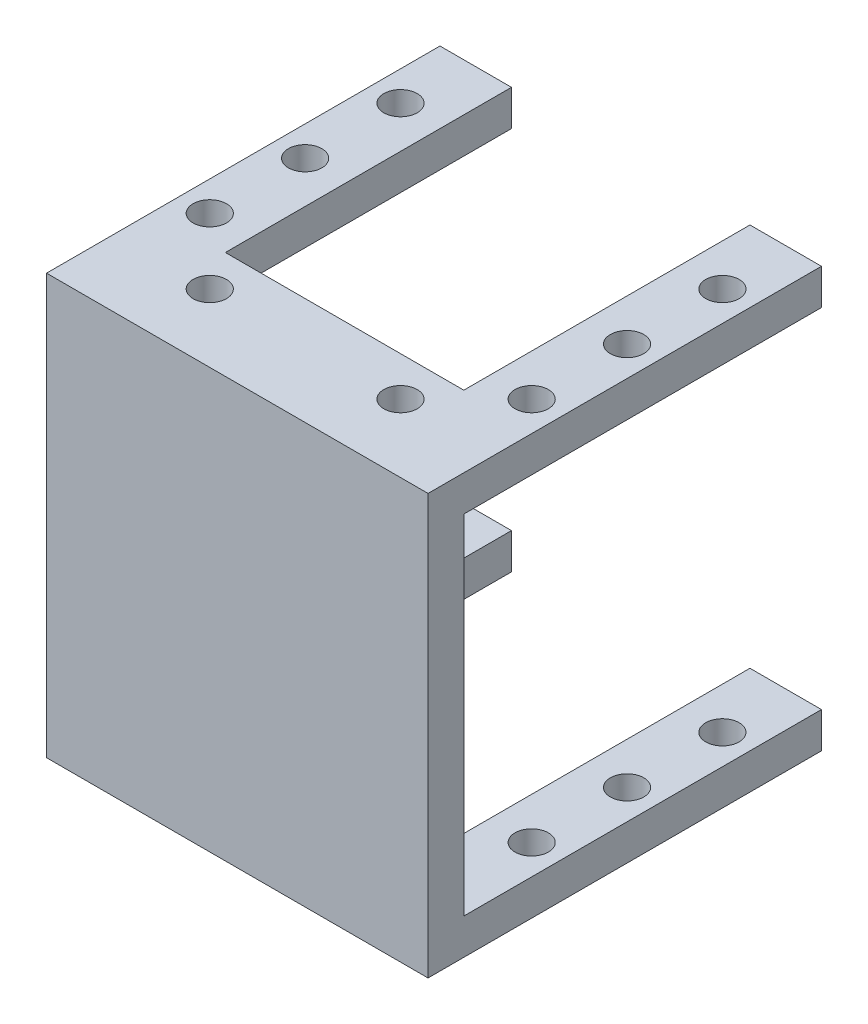
SolidWorks part; units mm, degrees
ref_plane "Front Plane" through (0, 0, 0) normal (0, 0, 1) x (1, 0, 0)
ref_plane "Top Plane" through (0, 0, 0) normal (0, 1, 0) x (1, 0, 0)
ref_plane "Right Plane" through (0, 0, 0) normal (1, 0, 0) x (0, 0, -1)
sketch "Sketch1" plane through (0, 0, 0) normal (0, 1, 0) x (1, 0, 0)
  line L0 (-16, 24) -> (-16, -6)
  line L1 (-16, -6) -> (16, -6)
  line L2 (16, -6) -> (16, 24)
  line L3 (16, 24) -> (10, 24)
  line L4 (10, 24) -> (10, 0)
  line L5 (10, 0) -> (-10, 0)
  line L6 (-10, 0) -> (-10, 24)
  line L7 (-10, 24) -> (-16, 24)
  line L8 (0, 0) -> (0, -6) construction
  circle A0 centre (-0.0169, 32.6923) radius 11 construction
  circle A1 centre (-8, -3.3077) radius 1.4
  circle A2 centre (8, -3.3077) radius 1.4
  circle A3 centre (-13.5, 26.1923) radius 1.4 construction
  circle A4 centre (-13.5, 18.1923) radius 1.4
  circle A5 centre (-13.5, 10.1923) radius 1.4
  circle A6 centre (-13.5, 2.1923) radius 1.4
  circle A7 centre (13.5, 2.1923) radius 1.4
  circle A8 centre (13.5, 10.1923) radius 1.4
  circle A9 centre (13.5, 18.1923) radius 1.4
  circle A10 centre (13.5, 26.1923) radius 1.4 construction
  point P4 (0, 0)
  dimension "D4" = 6
  dimension "D5" = 2.8
  dimension "D6" = 16
  dimension "D8" = 22
  dimension "D9" = 2.8
  dimension "D1" = 32
  dimension "D2" = 20
  dimension "D3" = 30
  dimension "D7" = 36
  dimension "D11" = 6.5
  dimension "D12" = 27
  dimension "D10" = 4
extrude "Boss-Extrude1" add sketch "Sketch1" along normal blind 3
ref_plane "Plane1" through (0, 32.2, 0) normal (0, 1, 0) x (1, 0, 0)
sketch "Sketch2" plane through (0, 32.2, 0) normal (0, 1, 0) x (1, 0, 0)
  line L0 (16, 24) -> (10, 24) construction
  line L1 (10, 24) -> (10, 0) construction
  line L2 (16, -6) -> (16, 24) construction
  line L3 (-16, -6) -> (16, -6) construction
  line L4 (10, 0) -> (-10, 0) construction
  line L5 (-10, 24) -> (-16, 24) construction
  line L6 (-10, 0) -> (-10, 24) construction
  line L7 (-16, 24) -> (-16, -6) construction
  line L8 (16, 24) -> (10, 24)
  line L9 (10, 24) -> (10, 0)
  line L10 (16, -6) -> (16, 24)
  line L11 (-16, -6) -> (16, -6)
  line L12 (10, 0) -> (-10, 0)
  line L13 (-10, 24) -> (-16, 24)
  line L14 (-10, 0) -> (-10, 24)
  line L15 (-16, 24) -> (-16, -6)
  circle A0 centre (-13.5, 18.1923) radius 1.4 construction
  circle A1 centre (-13.5, 18.1923) radius 1.4
  circle A2 centre (13.5, 18.1923) radius 1.4 construction
  circle A3 centre (13.5, 10.1923) radius 1.4 construction
  circle A4 centre (13.5, 2.1923) radius 1.4 construction
  circle A5 centre (8, -3.3077) radius 1.4 construction
  circle A6 centre (-8, -3.3077) radius 1.4 construction
  circle A7 centre (-13.5, 10.1923) radius 1.4 construction
  circle A8 centre (13.5, 18.1923) radius 1.4
  circle A9 centre (13.5, 10.1923) radius 1.4
  circle A10 centre (13.5, 2.1923) radius 1.4
  circle A11 centre (8, -3.3077) radius 1.4
  circle A12 centre (-8, -3.3077) radius 1.4
  circle A13 centre (-13.5, 10.1923) radius 1.4
  circle A14 centre (-13.5, 2.1923) radius 1.4 construction
  circle A15 centre (-13.5, 2.1923) radius 1.4
extrude "Boss-Extrude2" add sketch "Sketch2" along normal blind 3 separate body
sketch "Sketch3" plane through (0, 0, 6) normal (0, 0, 1) x (1, 0, 0)
  line L1 (-16, 35.2) -> (16, 35.2)
  line L2 (-16, 35.2) -> (-16, 0)
  line L3 (-16, 0) -> (16, 0)
  line L4 (16, 35.2) -> (16, 0)
  line L5 (0, 0) -> (0, 35.2) construction
  line L6 (-16, 17.6) -> (16, 17.6) construction
  point P216 (0, 17.6)
extrude "Boss-Extrude3" add sketch "Sketch3" along normal blind 3
ref_plane "Plane2" through (16, 0, 0) normal (1, 0, 0) x (0, 0, -1)
ref_plane "Plane3" through (0, 10, 0) normal (0, 1, 0) x (1, 0, 0)
